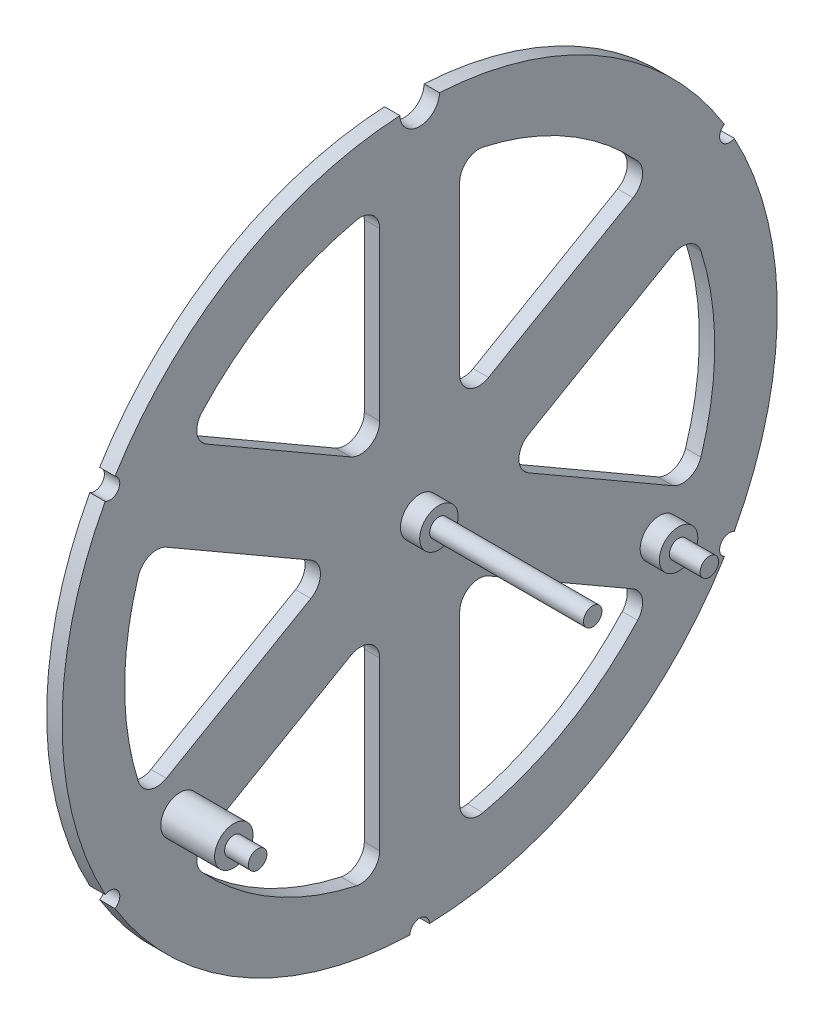
SolidWorks part; units mm, degrees
ref_plane "前视基准面" through (0, 0, 0) normal (0, 0, 1) x (1, 0, 0)
ref_plane "上视基准面" through (0, 0, 0) normal (0, 1, 0) x (1, 0, 0)
ref_plane "右视基准面" through (0, 0, 0) normal (1, 0, 0) x (0, 0, -1)
other "Configuration Table"
sketch "草图1" plane through (0, 0, 0) normal (1, 0, 0) x (0, 0, -1)
  circle A0 centre (0, 0) radius 93.03
extrude "凸台-拉伸1" add sketch "草图1" along normal blind 4
sketch "草图2" plane through (4, 0, 0) normal (1, 0, 0) x (0, 0, -1)
  circle A0 centre (0, 0) radius 2.4
  dimension "D1" = 4.8
extrude "凸台-拉伸2" add sketch "草图2" along normal blind 45
sketch "草图3" plane through (4, 0, 0) normal (1, 0, 0) x (0, 0, -1)
  circle A0 centre (0, 0) radius 5
  dimension "D1" = 10
extrude "凸台-拉伸3" add sketch "草图3" along normal blind 5
sketch "草图4" plane through (4, 0, 0) normal (1, 0, 0) x (0, 0, -1)
  line L0 (0, 0) -> (62.3538, -36) construction
  line L1 (0, 0) -> (0, -41.61) construction
  circle A0 centre (62.3538, -36) radius 2.4
  dimension "D1" = 4.8
  dimension "D2" = 72
  dimension "D3" = 60
extrude "凸台-拉伸4" add sketch "草图4" along normal blind 13
sketch "草图5" plane through (4, 0, 0) normal (1, 0, 0) x (0, 0, -1)
  circle A0 centre (62.3538, -36) radius 5
  dimension "D1" = 10
extrude "凸台-拉伸5" add sketch "草图5" along normal blind 5
sketch "草图6" plane through (4, 0, 0) normal (1, 0, 0) x (0, 0, -1)
  line L0 (0, 0) -> (0, -47.998) construction
  line L1 (-62.3538, -36) -> (0, 0) construction
  circle A0 centre (-62.3538, -36) radius 2.4
  dimension "D1" = 4.8
  dimension "D2" = 72
  dimension "D3" = 60
extrude "凸台-拉伸6" add sketch "草图6" along normal blind 20.2
sketch "草图7" plane through (4, 0, 0) normal (1, 0, 0) x (0, 0, -1)
  circle A0 centre (-62.3538, -36) radius 5
  dimension "D1" = 10
extrude "凸台-拉伸7" add sketch "草图7" along normal blind 14
sketch "草图8" plane through (4, 0, 0) normal (1, 0, 0) x (0, 0, -1)
  circle A0 centre (0, 93.03) radius 5.1532
  circle A1 centre (0, 0) radius 93.03 construction
  point P4 (0, 93.03)
extrude "切除-拉伸1" cut sketch "草图8" against normal up to next
sketch "草图9" plane through (4, 0, 0) normal (1, 0, 0) x (0, 0, -1)
  circle A0 centre (0, 93.03) radius 2.5515
  circle A1 centre (80.5664, 46.515) radius 2.5515
  circle A2 centre (80.5664, -46.515) radius 2.5515
  circle A3 centre (0, -93.03) radius 2.5515
  circle A4 centre (-80.5664, -46.515) radius 2.5515
  circle A5 centre (-80.5664, 46.515) radius 2.5515
  point P3 (0, 0)
  point P16 (0, 0)
  dimension "D1" = 6
extrude "切除-拉伸3" cut sketch "草图9" against normal blind 6
sketch "草图10" plane through (4, 0, 0) normal (1, 0, 0) x (0, 0, -1)
  line L0 (-27.1564, 47.0363) -> (0, 0) construction
  line L1 (-10.4075, 18.0263) -> (-10.4075, 76.0463)
  line L3 (-60.6542, 47.0363) -> (-10.4075, 18.0263)
  line L4 (0, 0) -> (0, 45.6618) construction
  line L6 (-10.4075, 76.0463) -> (-35.5309, 61.5413) [skipped]
  circle A0 centre (-27.1564, 47.0363) radius 16.7489 construction
  arc A1 (-60.6542, 47.0363) -> (-10.4075, 76.0463) centre (0, 0) cw
  dimension "D1" = 30
extrude "切除-拉伸4" cut sketch "草图10" against normal up to next
pattern_circular "阵列(圆周)1" count 6 over 360 about axis through (0, 0, 0) along (1, 0, 0) of "切除-拉伸4"
fillet "圆角1" radius 5 18 edges at (2, 18.0263, 10.4075) (2, 76.0463, 10.4075) (2, 47.0363, 60.6542) (2, 76.0463, -10.4075) (2, 47.0363, -60.6542) (2, 18.0263, -10.4075) (2, 0, -20.815) (2, -29.01, -71.0617) (2, 29.01, -71.0617) (2, -47.0363, -60.6542) (2, -76.0463, -10.4075) (2, -18.0263, -10.4075) (2, -76.0463, 10.4075) (2, -47.0363, 60.6542) (2, -18.0263, 10.4075) (2, 0, 20.815) (2, 29.01, 71.0617) (2, -29.01, 71.0617)
